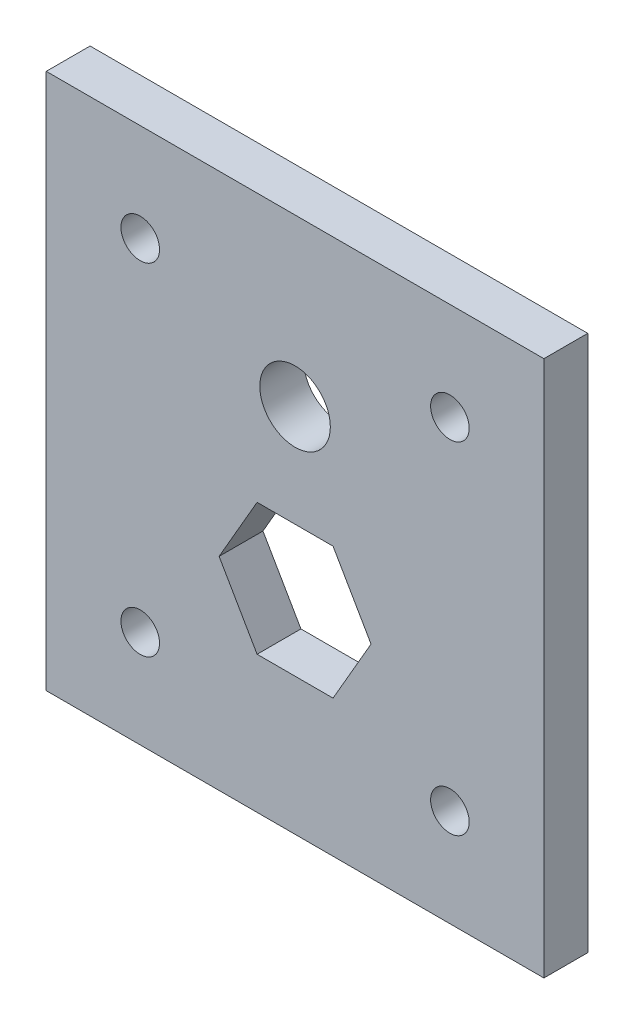
SolidWorks part; units mm, degrees
ref_plane "Front Plane" through (0, 0, 0) normal (0, 0, 1) x (1, 0, 0)
ref_plane "Top Plane" through (0, 0, 0) normal (0, 1, 0) x (1, 0, 0)
ref_plane "Right Plane" through (0, 0, 0) normal (1, 0, 0) x (0, 0, -1)
sketch "Sketch1" plane through (0, 0, 0) normal (0, 0, 1) x (1, 0, 0)
  line L0 (23.5034, -26.6844) -> (45.9189, -26.6844) construction
  line L1 (16.6987, 5.0709) -> (52.7236, 5.0709)
  line L2 (16.6987, 5.0709) -> (16.6987, -33.756)
  line L3 (16.6987, -33.756) -> (52.7236, -33.756)
  line L4 (52.7236, 5.0709) -> (52.7236, -33.756)
  line L5 (40.2104, -19.0791) -> (37.4608, -14.3166)
  line L6 (37.4608, -14.3166) -> (31.9615, -14.3166)
  line L7 (31.9615, -14.3166) -> (29.2119, -19.0791)
  line L8 (29.2119, -19.0791) -> (31.9615, -23.8416)
  line L9 (31.9615, -23.8416) -> (37.4608, -23.8416)
  line L10 (37.4608, -23.8416) -> (40.2104, -19.0791)
  line L11 (45.9189, -26.6844) -> (45.9189, -2.0006) construction
  line L12 (34.7111, -26.6844) -> (34.7111, -33.756) construction
  line L13 (45.9189, -14.3425) -> (52.7236, -14.3425) construction
  line L14 (34.7111, -6.9374) -> (34.7111, -19.0791) construction
  circle A0 centre (34.7111, -19.0791) radius 4.7625 construction
  circle A1 centre (45.9189, -2.0006) radius 1.397
  circle A2 centre (23.5034, -2.0006) radius 1.397
  circle A3 centre (23.5034, -26.6844) radius 1.397
  circle A4 centre (45.9189, -26.6844) radius 1.397
  circle A5 centre (34.7111, -6.9374) radius 2.5527
extrude "Boss-Extrude1" add sketch "Sketch1" along normal blind 3.175
